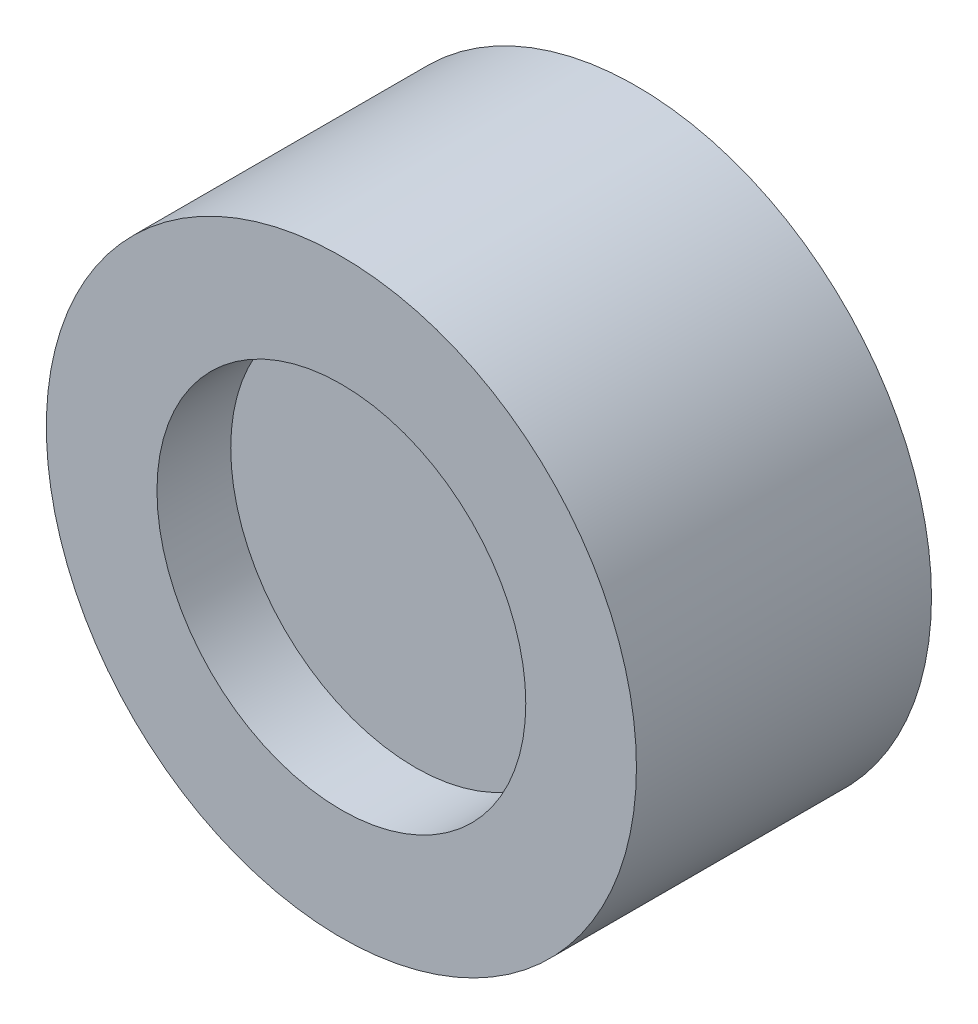
SolidWorks part; units mm, degrees
ref_plane "Front Plane" through (0, 0, 0) normal (0, 0, 1) x (1, 0, 0)
ref_plane "Top Plane" through (0, 0, 0) normal (0, 1, 0) x (1, 0, 0)
ref_plane "Right Plane" through (0, 0, 0) normal (1, 0, 0) x (0, 0, -1)
sketch "Sketch1" plane through (0, 0, 0) normal (0, 0, 1) x (1, 0, 0)
  circle A0 centre (0, 0) radius 20
  dimension "D1" = 40
extrude "Boss-Extrude1" add sketch "Sketch1" along normal mid plane 20
sketch "Sketch2" plane through (0, 0, 10) normal (0, 0, 1) x (1, 0, 0)
  circle A0 centre (0, 0) radius 12.5
  dimension "D1" = 25
extrude "Cut-Extrude1" cut sketch "Sketch2" against normal blind 5
